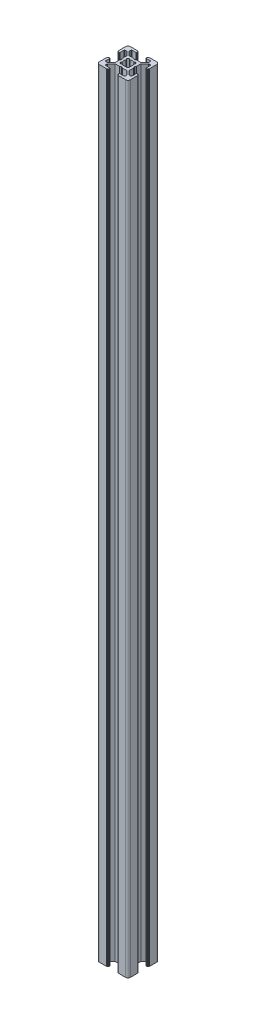
SolidWorks part; units mm, degrees
material "6061 Alloy"
ref_plane "Front Plane" through (0, 0, 0) normal (0, 0, 1) x (1, 0, 0)
ref_plane "Top Plane" through (0, 0, 0) normal (0, 1, 0) x (1, 0, 0)
ref_plane "Right Plane" through (0, 0, 0) normal (1, 0, 0) x (0, 0, -1)
sketch "Sketch2" plane through (0, 0, 0) normal (0, 1, 0) x (1, 0, 0)
  line L0 (-10, 3.75) -> (-10, 8.5)
  line L1 (10, -10) -> (-10, -10) construction
  line L2 (10, -10) -> (10, 10) construction
  line L3 (10, 10) -> (-10, 10) construction
  line L4 (-10, -10) -> (-10, 10) construction
  line L5 (10, -10) -> (-10, 10) construction
  line L6 (10, 10) -> (-10, -10) construction
  line L7 (-9.8, 3.55) -> (-9.7, 3.55)
  line L8 (-9.5, 3.35) -> (-9.5, 3.2)
  line L9 (-9.3, 3) -> (-8.9, 3)
  line L10 (-8.5, 3.4) -> (-8.5, 5.9)
  line L11 (-8.1, 6.3) -> (-7.1728, 6.3)
  line L12 (-6.8899, 6.1828) -> (-4.6172, 3.9101)
  line L13 (-4.5, 3.6272) -> (-4.5, 0.9196)
  line L14 (-4.4732, 0.8196) -> (-4.0577, 0.1)
  line L15 (-2.4797, 1.419) -> (-2.8968, 1.8361)
  line L16 (0, 0) -> (-10, 0) construction
  line L17 (-2.4797, -1.419) -> (-2.8968, -1.8361)
  line L18 (-4.4732, -0.8196) -> (-4.0577, -0.1)
  line L19 (-4.5, -3.6272) -> (-4.5, -0.9196)
  line L20 (-6.8899, -6.1828) -> (-4.6172, -3.9101)
  line L21 (-8.1, -6.3) -> (-7.1728, -6.3)
  line L22 (-8.5, -3.4) -> (-8.5, -5.9)
  line L23 (-9.3, -3) -> (-8.9, -3)
  line L24 (-9.5, -3.35) -> (-9.5, -3.2)
  line L25 (-9.8, -3.55) -> (-9.7, -3.55)
  line L26 (-10, -3.75) -> (-10, -8.5)
  line L27 (-6.3, 8.1) -> (-6.3, 7.1728)
  line L28 (1.419, 2.4797) -> (1.8361, 2.8968)
  line L29 (6.1828, 6.8899) -> (3.9101, 4.6172)
  line L30 (6.3, 8.1) -> (6.3, 7.1728)
  line L31 (3.75, 10) -> (8.5, 10)
  line L32 (3.55, 9.8) -> (3.55, 9.7)
  line L33 (3.35, 9.5) -> (3.2, 9.5)
  line L34 (3, 9.3) -> (3, 8.9)
  line L35 (3.4, 8.5) -> (5.9, 8.5)
  line L36 (3.6272, 4.5) -> (0.9196, 4.5)
  line L37 (0.8196, 4.4732) -> (0.1, 4.0577)
  line L38 (-0.8196, 4.4732) -> (-0.1, 4.0577)
  line L39 (-1.419, 2.4797) -> (-1.8361, 2.8968)
  line L40 (-3.6272, 4.5) -> (-0.9196, 4.5)
  line L41 (-6.1828, 6.8899) -> (-3.9101, 4.6172)
  line L42 (-3.4, 8.5) -> (-5.9, 8.5)
  line L43 (-3, 9.3) -> (-3, 8.9)
  line L44 (-3.35, 9.5) -> (-3.2, 9.5)
  line L45 (-3.55, 9.8) -> (-3.55, 9.7)
  line L46 (-3.75, 10) -> (-8.5, 10)
  line L47 (10, -3.75) -> (10, -8.5)
  line L48 (9.8, -3.55) -> (9.7, -3.55)
  line L49 (9.5, -3.35) -> (9.5, -3.2)
  line L50 (9.3, -3) -> (8.9, -3)
  line L51 (8.5, -3.4) -> (8.5, -5.9)
  line L52 (6.8899, -6.1828) -> (4.6172, -3.9101)
  line L53 (4.5, -3.6272) -> (4.5, -0.9196)
  line L54 (2.4797, -1.419) -> (2.8968, -1.8361)
  line L55 (4.4732, -0.8196) -> (4.0577, -0.1)
  line L56 (4.4732, 0.8196) -> (4.0577, 0.1)
  line L57 (4.5, 3.6272) -> (4.5, 0.9196)
  line L58 (8.5, 3.4) -> (8.5, 5.9)
  line L59 (9.3, 3) -> (8.9, 3)
  line L60 (9.5, 3.35) -> (9.5, 3.2)
  line L61 (9.8, 3.55) -> (9.7, 3.55)
  line L62 (10, 3.75) -> (10, 8.5)
  line L63 (8.1, 6.3) -> (7.1728, 6.3)
  line L64 (6.8899, 6.1828) -> (4.6172, 3.9101)
  line L65 (2.4797, 1.419) -> (2.8968, 1.8361)
  line L66 (8.1, -6.3) -> (7.1728, -6.3)
  line L67 (-3.75, -10) -> (-8.5, -10)
  line L68 (-3.55, -9.8) -> (-3.55, -9.7)
  line L69 (-3.35, -9.5) -> (-3.2, -9.5)
  line L70 (-3, -9.3) -> (-3, -8.9)
  line L71 (-3.4, -8.5) -> (-5.9, -8.5)
  line L72 (-6.3, -8.1) -> (-6.3, -7.1728)
  line L73 (-6.1828, -6.8899) -> (-3.9101, -4.6172)
  line L74 (-3.6272, -4.5) -> (-0.9196, -4.5)
  line L75 (-0.8196, -4.4732) -> (-0.1, -4.0577)
  line L76 (-1.419, -2.4797) -> (-1.8361, -2.8968)
  line L77 (1.419, -2.4797) -> (1.8361, -2.8968)
  line L78 (0.8196, -4.4732) -> (0.1, -4.0577)
  line L79 (3.6272, -4.5) -> (0.9196, -4.5)
  line L80 (6.1828, -6.8899) -> (3.9101, -4.6172)
  line L81 (6.3, -8.1) -> (6.3, -7.1728)
  line L82 (3.4, -8.5) -> (5.9, -8.5)
  line L83 (3, -9.3) -> (3, -8.9)
  line L84 (3.35, -9.5) -> (3.2, -9.5)
  line L85 (3.55, -9.8) -> (3.55, -9.7)
  line L86 (3.75, -10) -> (8.5, -10)
  arc A0 (-10, 8.5) -> (-8.5, 10) centre (-8.5, 8.5) cw
  arc A1 (-2.452, -1.2451) -> (-2.452, 1.2451) centre (0, 0) cw
  arc A2 (-2.9138, 2.0279) -> (-2.0279, 2.9138) centre (0, 0) cw
  arc A3 (-2.9138, -2.0279) -> (-2.0279, -2.9138) centre (0, 0) ccw
  arc A4 (-10, -8.5) -> (-8.5, -10) centre (-8.5, -8.5) ccw
  arc A5 (2.0279, 2.9138) -> (2.9138, 2.0279) centre (0, 0) cw
  arc A6 (8.5, 10) -> (10, 8.5) centre (8.5, 8.5) cw
  arc A7 (1.2451, 2.452) -> (-1.2451, 2.452) centre (0, 0) ccw
  arc A8 (2.452, 1.2451) -> (2.452, -1.2451) centre (0, 0) cw
  arc A9 (2.0279, -2.9138) -> (2.9138, -2.0279) centre (0, 0) ccw
  arc A10 (-1.2451, -2.452) -> (1.2451, -2.452) centre (0, 0) ccw
  arc A11 (8.5, -10) -> (10, -8.5) centre (8.5, -8.5) ccw
  arc A12 (-3.55, 9.8) -> (-3.75, 10) centre (-3.75, 9.8) ccw
  arc A13 (-3.35, 9.5) -> (-3.55, 9.7) centre (-3.35, 9.7) cw
  arc A14 (-3, 9.3) -> (-3.2, 9.5) centre (-3.2, 9.3) ccw
  arc A15 (3.75, 10) -> (3.55, 9.8) centre (3.75, 9.8) ccw
  arc A16 (3.2, 9.5) -> (3, 9.3) centre (3.2, 9.3) ccw
  arc A17 (3.55, 9.7) -> (3.35, 9.5) centre (3.35, 9.7) cw
  arc A18 (9.8, 3.55) -> (10, 3.75) centre (9.8, 3.75) ccw
  arc A19 (9.5, 3.35) -> (9.7, 3.55) centre (9.7, 3.35) cw
  arc A20 (9.3, 3) -> (9.5, 3.2) centre (9.3, 3.2) ccw
  arc A21 (9.5, -3.2) -> (9.3, -3) centre (9.3, -3.2) ccw
  arc A22 (9.7, -3.55) -> (9.5, -3.35) centre (9.7, -3.35) cw
  arc A23 (10, -3.75) -> (9.8, -3.55) centre (9.8, -3.75) ccw
  arc A24 (3.55, -9.8) -> (3.75, -10) centre (3.75, -9.8) ccw
  arc A25 (3.35, -9.5) -> (3.55, -9.7) centre (3.35, -9.7) cw
  arc A26 (3, -9.3) -> (3.2, -9.5) centre (3.2, -9.3) ccw
  arc A27 (-3.75, -10) -> (-3.55, -9.8) centre (-3.75, -9.8) ccw
  arc A28 (-3.55, -9.7) -> (-3.35, -9.5) centre (-3.35, -9.7) cw
  arc A29 (-3.2, -9.5) -> (-3, -9.3) centre (-3.2, -9.3) ccw
  arc A30 (4.4732, 0.8196) -> (4.5, 0.9196) centre (4.3, 0.9196) ccw
  arc A31 (4.0577, -0.1) -> (4.0577, 0.1) centre (4.2309, 0) cw
  arc A32 (4.5, -0.9196) -> (4.4732, -0.8196) centre (4.3, -0.9196) ccw
  arc A33 (0.8196, -4.4732) -> (0.9196, -4.5) centre (0.9196, -4.3) ccw
  arc A34 (-0.1, -4.0577) -> (0.1, -4.0577) centre (0, -4.2309) cw
  arc A35 (-0.9196, -4.5) -> (-0.8196, -4.4732) centre (-0.9196, -4.3) ccw
  arc A36 (-4.4732, -0.8196) -> (-4.5, -0.9196) centre (-4.3, -0.9196) ccw
  arc A37 (-4.0577, 0.1) -> (-4.0577, -0.1) centre (-4.2309, 0) cw
  arc A38 (-4.5, 0.9196) -> (-4.4732, 0.8196) centre (-4.3, 0.9196) ccw
  arc A39 (0.9196, 4.5) -> (0.8196, 4.4732) centre (0.9196, 4.3) ccw
  arc A40 (0.1, 4.0577) -> (-0.1, 4.0577) centre (0, 4.2309) cw
  arc A41 (-0.8196, 4.4732) -> (-0.9196, 4.5) centre (-0.9196, 4.3) ccw
  arc A42 (-9.8, -3.55) -> (-10, -3.75) centre (-9.8, -3.75) ccw
  arc A43 (-9.5, -3.35) -> (-9.7, -3.55) centre (-9.7, -3.35) cw
  arc A44 (-9.3, -3) -> (-9.5, -3.2) centre (-9.3, -3.2) ccw
  arc A45 (-9.5, 3.2) -> (-9.3, 3) centre (-9.3, 3.2) ccw
  arc A46 (-9.7, 3.55) -> (-9.5, 3.35) centre (-9.7, 3.35) cw
  arc A47 (-10, 3.75) -> (-9.8, 3.55) centre (-9.8, 3.75) ccw
  arc A48 (-8.9, 3) -> (-8.5, 3.4) centre (-8.9, 3.4) ccw
  arc A49 (-8.5, 5.9) -> (-8.1, 6.3) centre (-8.1, 5.9) cw
  arc A50 (-3.4, 8.5) -> (-3, 8.9) centre (-3.4, 8.9) ccw
  arc A51 (-6.3, 8.1) -> (-5.9, 8.5) centre (-5.9, 8.1) cw
  arc A52 (-6.3, 7.1728) -> (-6.1828, 6.8899) centre (-5.9, 7.1728) ccw
  arc A53 (-7.1728, 6.3) -> (-6.8899, 6.1828) centre (-7.1728, 5.9) cw
  arc A54 (-4.6172, 3.9101) -> (-4.5, 3.6272) centre (-4.9, 3.6272) cw
  arc A55 (-3.6272, 4.5) -> (-3.9101, 4.6172) centre (-3.6272, 4.9) cw
  arc A56 (8.5, 3.4) -> (8.9, 3) centre (8.9, 3.4) ccw
  arc A57 (8.5, 5.9) -> (8.1, 6.3) centre (8.1, 5.9) ccw
  arc A58 (7.1728, 6.3) -> (6.8899, 6.1828) centre (7.1728, 5.9) ccw
  arc A59 (3, 8.9) -> (3.4, 8.5) centre (3.4, 8.9) ccw
  arc A60 (6.3, 8.1) -> (5.9, 8.5) centre (5.9, 8.1) ccw
  arc A61 (6.1828, 6.8899) -> (6.3, 7.1728) centre (5.9, 7.1728) ccw
  arc A62 (3.9101, 4.6172) -> (3.6272, 4.5) centre (3.6272, 4.9) cw
  arc A63 (4.5, 3.6272) -> (4.6172, 3.9101) centre (4.9, 3.6272) cw
  arc A64 (8.9, -3) -> (8.5, -3.4) centre (8.9, -3.4) ccw
  arc A65 (8.5, -5.9) -> (8.1, -6.3) centre (8.1, -5.9) cw
  arc A66 (6.8899, -6.1828) -> (7.1728, -6.3) centre (7.1728, -5.9) ccw
  arc A67 (4.6172, -3.9101) -> (4.5, -3.6272) centre (4.9, -3.6272) cw
  arc A68 (3.6272, -4.5) -> (3.9101, -4.6172) centre (3.6272, -4.9) cw
  arc A69 (6.1828, -6.8899) -> (6.3, -7.1728) centre (5.9, -7.1728) cw
  arc A70 (6.3, -8.1) -> (5.9, -8.5) centre (5.9, -8.1) cw
  arc A71 (3.4, -8.5) -> (3, -8.9) centre (3.4, -8.9) ccw
  arc A72 (-3, -8.9) -> (-3.4, -8.5) centre (-3.4, -8.9) ccw
  arc A73 (-5.9, -8.5) -> (-6.3, -8.1) centre (-5.9, -8.1) cw
  arc A74 (-6.3, -7.1728) -> (-6.1828, -6.8899) centre (-5.9, -7.1728) cw
  arc A75 (-3.9101, -4.6172) -> (-3.6272, -4.5) centre (-3.6272, -4.9) cw
  arc A76 (-4.5, -3.6272) -> (-4.6172, -3.9101) centre (-4.9, -3.6272) cw
  arc A77 (-6.8899, -6.1828) -> (-7.1728, -6.3) centre (-7.1728, -5.9) cw
  arc A78 (-8.1, -6.3) -> (-8.5, -5.9) centre (-8.1, -5.9) cw
  arc A79 (-8.5, -3.4) -> (-8.9, -3) centre (-8.9, -3.4) ccw
  arc A80 (-2.4797, -1.419) -> (-2.452, -1.2451) centre (-2.5858, -1.313) ccw
  arc A81 (-2.9138, -2.0279) -> (-2.8968, -1.8361) centre (-2.7907, -1.9422) cw
  arc A82 (-1.8361, -2.8968) -> (-2.0279, -2.9138) centre (-1.9422, -2.7907) cw
  arc A83 (-1.2451, -2.452) -> (-1.419, -2.4797) centre (-1.313, -2.5858) ccw
  arc A84 (1.2451, -2.452) -> (1.419, -2.4797) centre (1.313, -2.5858) cw
  arc A85 (2.0279, -2.9138) -> (1.8361, -2.8968) centre (1.9422, -2.7907) cw
  arc A86 (2.9138, -2.0279) -> (2.8968, -1.8361) centre (2.7907, -1.9422) ccw
  arc A87 (2.452, -1.2451) -> (2.4797, -1.419) centre (2.5858, -1.313) ccw
  arc A88 (2.452, 1.2451) -> (2.4797, 1.419) centre (2.5858, 1.313) cw
  arc A89 (2.8968, 1.8361) -> (2.9138, 2.0279) centre (2.7907, 1.9422) ccw
  arc A90 (2.0279, 2.9138) -> (1.8361, 2.8968) centre (1.9422, 2.7907) ccw
  arc A91 (1.419, 2.4797) -> (1.2451, 2.452) centre (1.313, 2.5858) cw
  arc A92 (-1.2451, 2.452) -> (-1.419, 2.4797) centre (-1.313, 2.5858) cw
  arc A93 (-1.8361, 2.8968) -> (-2.0279, 2.9138) centre (-1.9422, 2.7907) ccw
  arc A94 (-2.8968, 1.8361) -> (-2.9138, 2.0279) centre (-2.7907, 1.9422) cw
  arc A95 (-2.452, 1.2451) -> (-2.4797, 1.419) centre (-2.5858, 1.313) ccw
  point P0 (0, 0)
  point P119 (-3.55, 10)
  point P122 (-3.55, 9.5)
  point P125 (-3, 9.5)
  point P128 (3.55, 10)
  point P131 (3, 9.5)
  point P134 (3.55, 9.5)
  point P137 (10, 3.55)
  point P140 (9.5, 3.55)
  point P143 (9.5, 3)
  point P146 (9.5, -3)
  point P149 (9.5, -3.55)
  point P152 (10, -3.55)
  point P155 (3.55, -10)
  point P158 (3.55, -9.5)
  point P161 (3, -9.5)
  point P164 (-3.55, -10)
  point P167 (-3.55, -9.5)
  point P170 (-3, -9.5)
  point P173 (4.5, 0.866)
  point P176 (4, 0)
  point P179 (4.5, -0.866)
  point P182 (0.866, -4.5)
  point P185 (0, -4)
  point P188 (-0.866, -4.5)
  point P191 (-4.5, -0.866)
  point P194 (-4, 0)
  point P197 (-4.5, 0.866)
  point P200 (0.866, 4.5)
  point P203 (0, 4)
  point P206 (-0.866, 4.5)
  point P209 (-10, -3.55)
  point P212 (-9.5, -3.55)
  point P215 (-9.5, -3)
  point P218 (-9.5, 3)
  point P221 (-9.5, 3.55)
  point P224 (-10, 3.55)
  point P227 (-8.5, 3)
  point P230 (-8.5, 6.3)
  point P233 (-3, 8.5)
  point P236 (-6.3, 8.5)
  point P239 (-6.3, 7.0071)
  point P242 (-7.0071, 6.3)
  point P245 (-4.5, 3.7929)
  point P248 (-3.7929, 4.5)
  point P251 (8.5, 3)
  point P254 (8.5, 6.3)
  point P257 (7.0071, 6.3)
  point P260 (3, 8.5)
  point P263 (6.3, 8.5)
  point P266 (6.3, 7.0071)
  point P269 (3.7929, 4.5)
  point P272 (4.5, 3.7929)
  point P275 (8.5, -3)
  point P278 (8.5, -6.3)
  point P281 (7.0071, -6.3)
  point P284 (4.5, -3.7929)
  point P287 (3.7929, -4.5)
  point P290 (6.3, -7.0071)
  point P293 (6.3, -8.5)
  point P296 (3, -8.5)
  point P299 (-3, -8.5)
  point P302 (-6.3, -8.5)
  point P305 (-6.3, -7.0071)
  point P308 (-3.7929, -4.5)
  point P311 (-4.5, -3.7929)
  point P314 (-7.0071, -6.3)
  point P317 (-8.5, -6.3)
  point P320 (-8.5, -3)
  point P323 (-2.4012, -1.3405)
  point P326 (-2.9839, -1.9232)
  point P329 (-1.9232, -2.9839)
  point P332 (-1.3405, -2.4012)
  point P335 (1.3405, -2.4012)
  point P338 (1.9232, -2.9839)
  point P341 (2.9839, -1.9232)
  point P344 (2.4012, -1.3405)
  point P347 (2.4012, 1.3405)
  point P350 (2.9839, 1.9232)
  point P353 (1.9232, 2.9839)
  point P356 (1.3405, 2.4012)
  point P359 (-1.3405, 2.4012)
  point P362 (-1.9232, 2.9839)
  point P365 (-2.9839, 1.9232)
  point P368 (-2.4012, 1.3405)
  dimension "D3" = 1.5
  dimension "D10" = 2.75
  dimension "D11" = 3.55
  dimension "D16" = 0.2
  dimension "D17" = 0.4
  dimension "D18" = 0.15
  dimension "D1" = 20
  dimension "D2" = 20
  dimension "D4" = 6.45
  dimension "D5" = 0.5
  dimension "D6" = 1
  dimension "D7" = 7
  dimension "D8" = 4
  dimension "D9" = 1
  dimension "D12" = 1.5
  dimension "D13" = 3.3
  dimension "D14" = 4
  dimension "D15" = 60
extrude "Boss-Extrude1" add sketch "Sketch2" along normal mid plane 500 contours A95 A1 A80 L17 A81 A3 A82 L76 A83 A10 A84 L77 A85 A9 A86 L54 A87 A8 A88 L65 A89 A5 A90 L28 A91 A7 A92 L39 A93 A2 A94 L15 | L10 A49 L11 A53 L12 A54 L13 A38 L14 A37 L18 A36 L19 A76 L20 A77 L21 A78 L22 A79 L23 A44 L24 A43 L25 A42 L26 A4 L67 A27 L68 A28 L69 A29 L70 A72 L71 A73 L72 A74 L73 A75 L74 A35 L75 A34 L78 A33 L79 A68 L80 A69 L81 A70 L82 A71 L83 A26 L84 A25 L85 A24 L86 A11 L47 A23 L48 A22 L49 A21 L50 A64 L51 A65 L66 A66 L52 A67 L53 A32 L55 A31 L56 A30 L57 A63 L64 A58 L63 A57 L58 A56 L59 A20 L60 A19 L61 A18 L62 A6 L31 A15 L32 A17 L33 A16 L34 A59 L35 A60 L30 A61 L29 A62 L36 A39 L37 A40 L38 A41 L40 A55 L41 A52 L27 A51 L42 A50 L43 A14 L44 A13 L45 A12 L46 A0 L0 A47 L7 A46 L8 A45 L9 A48
